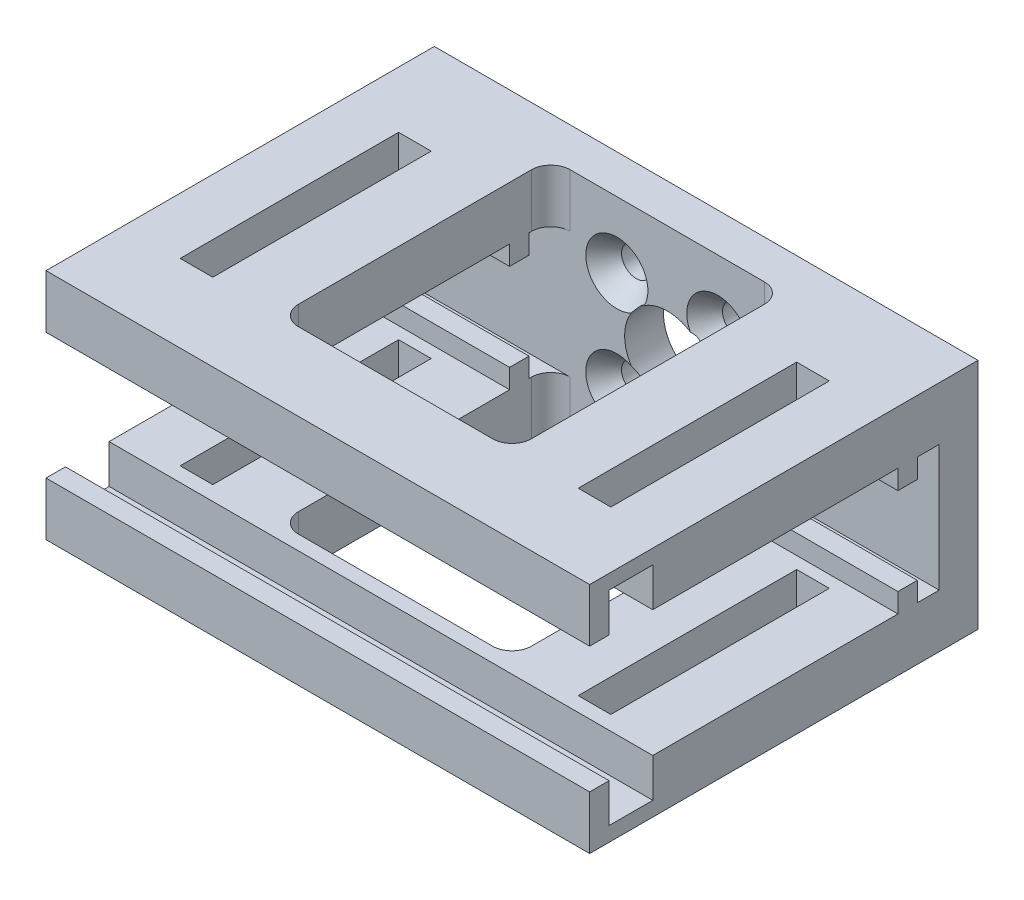
SolidWorks part; units mm, degrees
material "1023 Carbon Steel Sheet (SS)"
ref_plane "Front Plane" through (0, 0, 0) normal (0, 0, 1) x (1, 0, 0)
ref_plane "Top Plane" through (0, 0, 0) normal (0, 1, 0) x (1, 0, 0)
ref_plane "Right Plane" through (0, 0, 0) normal (1, 0, 0) x (0, 0, -1)
sketch "Sketch1" plane through (0, 0, 0) normal (0, 1, 0) x (1, 0, 0)
  line L1 (44.45, -31.75) -> (-44.45, -31.75)
  line L2 (44.45, -31.75) -> (44.45, 31.75)
  line L3 (44.45, 31.75) -> (-44.45, 31.75)
  line L4 (-44.45, -31.75) -> (-44.45, 31.75)
  line L5 (44.45, -31.75) -> (-44.45, 31.75) construction
  line L6 (44.45, 31.75) -> (-44.45, -31.75) construction
  point P0 (0, 0)
  dimension "D1" = 88.9
  dimension "D2" = 63.5
extrude "Boss-Extrude1" add sketch "Sketch1" along normal mid plane 38.1
sketch "Sketch3" plane through (44.45, 0, 0) normal (1, 0, 0) x (0, 0, -1)
  line L0 (-31.75, 19.05) -> (-31.75, -19.05) construction
  line L1 (-31.75, -10.3187) -> (25.4, -10.3187)
  line L2 (-31.75, -10.3187) -> (-31.75, 10.3187)
  line L3 (-31.75, 10.3187) -> (25.4, 10.3188)
  line L4 (25.4, -10.3187) -> (25.4, 10.3188)
  line L5 (-31.75, 19.05) -> (-31.75, -19.05) construction
  line L6 (31.75, 19.05) -> (31.75, -19.05) construction
  line L7 (-28.575, 10.3187) -> (-21.4312, 10.3187)
  line L8 (-28.575, 10.3187) -> (-28.575, 16.6687)
  line L9 (-28.575, 16.6687) -> (-21.4313, 16.6687)
  line L10 (-21.4312, 10.3187) -> (-21.4313, 16.6687)
  line L11 (-28.575, -10.3187) -> (-21.4312, -10.3187)
  line L12 (-28.575, -10.3187) -> (-28.575, -16.6687)
  line L13 (-28.575, -16.6687) -> (-21.4312, -16.6687)
  line L14 (-21.4312, -10.3187) -> (-21.4312, -16.6687)
  line L16 (18.6531, 10.3188) -> (21.8281, 10.3188)
  line L17 (18.6531, 10.3188) -> (18.6531, 7.1438)
  line L18 (18.6531, 7.1438) -> (21.8281, 7.1438)
  line L19 (21.8281, 10.3188) -> (21.8281, 7.1438)
  line L20 (18.6531, -10.3187) -> (21.8281, -10.3187)
  line L21 (18.6531, -10.3187) -> (18.6531, -7.1437)
  line L22 (18.6531, -7.1437) -> (21.8281, -7.1437)
  line L23 (21.8281, -10.3187) -> (21.8281, -7.1437)
  point P10 (-31.75, 0)
  point P11 (-31.75, 0)
  line M16 (-31.75, 19.05) -> (-31.75, -19.05)
  dimension "D1" = 6.35
  dimension "D2" = 7.1437
  dimension "D3" = 3.175
  dimension "D4" = 20.6375
  dimension "D5" = 6.35
  dimension "D6" = 3.175
  dimension "D7" = 3.5719
extrude "Cut-Extrude1" cut sketch "Sketch3" against normal through all contours L1 L4 L3 M16 | L3 L10 L9 L8 | L14 L1 L12 L13
sketch "Sketch7" plane through (0, 19.05, 0) normal (0, 1, 0) x (1, 0, 0)
  line L0 (-29.8768, -19.05) -> (29.8768, -19.05) construction
  line L1 (-35.2107, 16.6687) -> (-29.8768, 16.6687)
  line L2 (-35.2107, 16.6687) -> (-35.2107, -19.05)
  line L3 (-35.2107, -19.05) -> (-29.8768, -19.05)
  line L4 (-29.8768, 16.6687) -> (-29.8768, -19.05)
  line L5 (29.8768, 16.6687) -> (35.2107, 16.6687)
  line L6 (29.8768, 16.6687) -> (29.8768, -19.05)
  line L7 (29.8768, -19.05) -> (35.2107, -19.05)
  line L8 (35.2107, 16.6687) -> (35.2107, -19.05)
  line L9 (-44.45, -31.75) -> (44.45, -31.75) construction
  line L10 (44.45, 31.75) -> (-44.45, 31.75) construction
  line L11 (-19.05, 25.4) -> (19.05, 25.4)
  line L12 (-19.05, 25.4) -> (-19.05, -19.05)
  line L13 (-19.05, -19.05) -> (19.05, -19.05)
  line L14 (19.05, 25.4) -> (19.05, -19.05)
  point P8 (-32.5437, -19.05)
  point P9 (32.5437, -19.05)
  point P11 (0, -19.05)
  point P19 (0, -19.05)
  dimension "D1" = 65.0875
  dimension "D2" = 5.334
  dimension "D3" = 12.7
  dimension "D4" = 35.7188
  dimension "D5" = 38.1
  dimension "D6" = 6.35
extrude "Cut-Extrude4" cut sketch "Sketch7" against normal through all
sketch "Sketch4" plane through (0, 0, -25.4) normal (0, 0, 1) x (1, 0, 0)
  line L1 (8.255, -8.255) -> (-8.255, -8.255)
  line L2 (8.255, -8.255) -> (8.255, 8.255)
  line L3 (8.255, 8.255) -> (-8.255, 8.255)
  line L4 (-8.255, -8.255) -> (-8.255, 8.255)
  line L5 (8.255, -8.255) -> (-8.255, 8.255) construction
  line L6 (8.255, 8.255) -> (-8.255, -8.255) construction
  circle A0 centre (0, 0) radius 6.985
  circle A1 centre (-8.255, 8.255) radius 2.413
  circle A2 centre (8.255, 8.255) radius 2.413
  circle A3 centre (8.255, -8.255) radius 2.413
  circle A4 centre (-8.255, -8.255) radius 2.413
  point P0 (0, 0)
  dimension "D1" = 16.51
  dimension "D2" = 4.826
  dimension "D3" = 13.97
extrude "Cut-Extrude3" cut sketch "Sketch4" against normal through all contours A0 | L4 A1 L3 | L3 A1 L4 | L3 A2 L2 | L2 A2 L3 | L1 A3 L2 | L2 A3 L1 | L4 A4 L1 | L1 A4 L4
sketch "Sketch5" plane through (0, 0, -25.4) normal (0, 0, 1) x (1, 0, 0)
  circle A0 centre (-8.255, 8.255) radius 5.08
  circle A1 centre (8.255, 8.255) radius 5.08
  circle A2 centre (8.255, -8.255) radius 5.08
  circle A3 centre (-8.255, -8.255) radius 5.08
  dimension "D1" = 10.16
ref_plane "Plane1" through (0, 0, -28.575) normal (0, 0, 1) x (1, 0, 0)
sketch "Sketch6" plane through (0, 0, -28.575) normal (0, 0, 1) x (1, 0, 0)
  circle A0 centre (-8.255, 8.255) radius 2.413
  circle A1 centre (8.255, 8.255) radius 2.413
  circle A2 centre (8.255, -8.255) radius 2.413
  circle A3 centre (-8.255, -8.255) radius 2.413
  circle A4 centre (-8.255, 8.255) radius 2.413 construction
loft "Cut-Loft2" cut section "Sketch6" section "Sketch5"
pattern_circular "CirPattern1" count 4 every 90 about axis through (0, 0, 0) along (0, 0, 1) of "Cut-Loft2"
fillet "Fillet1" radius 3.175 8 edges at (-19.05, -14.6844, -25.4) (-19.05, 14.6844, -25.4) (19.05, -14.6844, -25.4) (19.05, 14.6844, -25.4) (-19.05, -14.6844, 19.05) (-19.05, 14.6844, 19.05) (19.05, -14.6844, 19.05) (19.05, 14.6844, 19.05)
